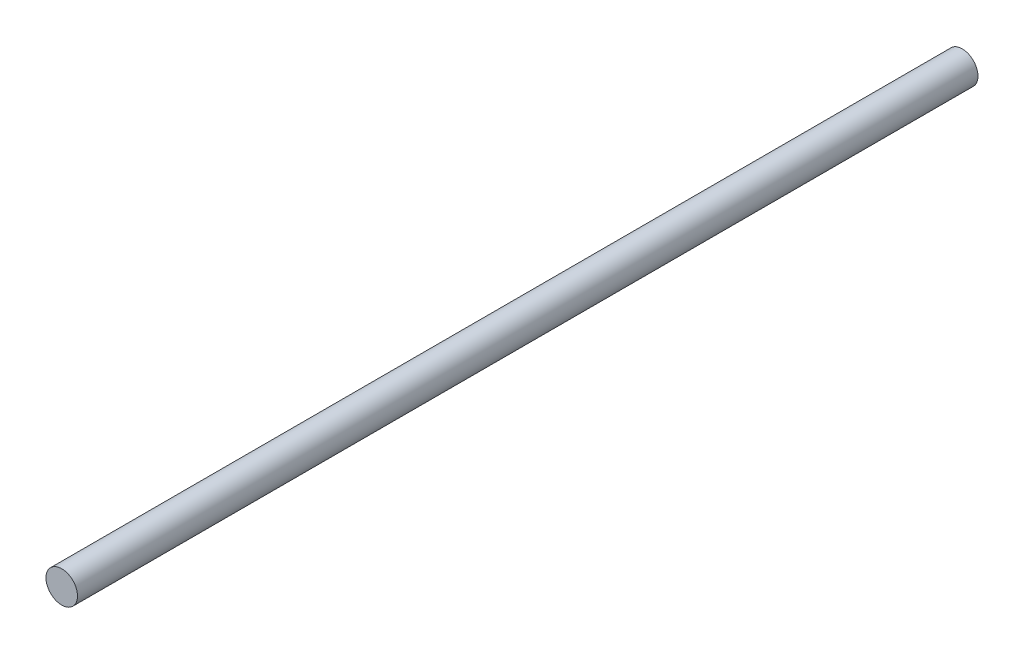
SolidWorks part; units mm, degrees
ref_plane "Front Plane" through (0, 0, 0) normal (0, 0, 1) x (1, 0, 0)
ref_plane "Top Plane" through (0, 0, 0) normal (0, 1, 0) x (1, 0, 0)
ref_plane "Right Plane" through (0, 0, 0) normal (1, 0, 0) x (0, 0, -1)
sketch "Sketch1" plane through (0, 0, 0) normal (0, 0, 1) x (1, 0, 0)
  circle A0 centre (0, 0) radius 4
  dimension "D1" = 8
extrude "Boss-Extrude1" add sketch "Sketch1" along normal blind 228.5
